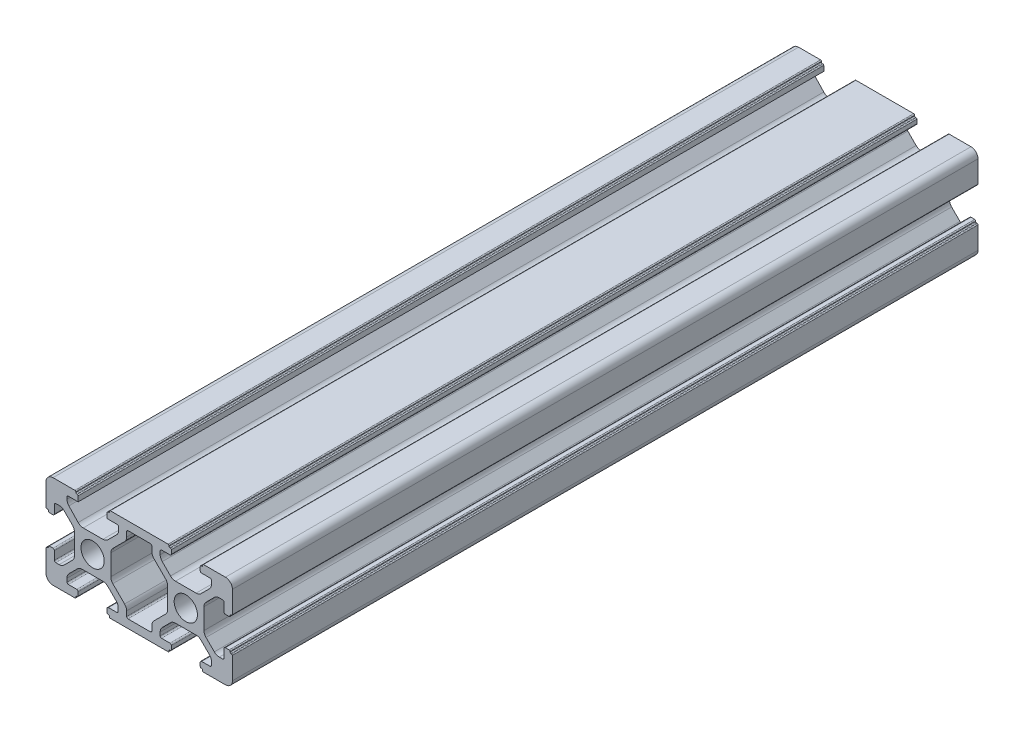
SolidWorks part; units mm, degrees
material "6063-T5"
ref_plane "Front Plane" through (0, 0, 0) normal (0, 0, 1) x (1, 0, 0)
ref_plane "Top Plane" through (0, 0, 0) normal (0, 1, 0) x (1, 0, 0)
ref_plane "Right Plane" through (0, 0, 0) normal (1, 0, 0) x (0, 0, -1)
sketch "Sketch1" plane through (0, 0, 0) normal (0, 0, 1) x (1, 0, 0)
  line L0 (1.5, 0) -> (6.2, 0)
  line L1 (40, 1.5) -> (40, 6.2)
  line L2 (38.5, 20) -> (33.8, 20)
  line L3 (0, 18.5) -> (0, 13.8)
  line L4 (17.6, 1.8) -> (22.4, 1.8)
  line L5 (32.218, 13.9) -> (27.782, 13.9)
  line L6 (26.1, 12.218) -> (26.1, 7.782)
  line L7 (17.6, 18.2) -> (22.4, 18.2)
  line L8 (12.218, 13.9) -> (7.9864, 13.9)
  line L9 (6.1, 12.218) -> (6.1, 7.782)
  line L10 (7.782, 6.1) -> (12.218, 6.1)
  line L11 (13.9, 7.782) -> (13.9, 12.218)
  line L12 (27.782, 6.1) -> (32.218, 6.1)
  line L13 (33.9, 7.782) -> (33.9, 12.218)
  line L14 (26.7213, 14.3393) -> (24.9393, 16.1213)
  line L15 (33.2787, 14.3393) -> (35.0607, 16.1213)
  line L16 (34.3393, 13.2787) -> (36.1213, 15.0607)
  line L17 (25.6607, 6.7213) -> (23.1393, 4.2)
  line L18 (15.2, 1.8) -> (13.4, 1.8)
  line L19 (26.7213, 5.6607) -> (24.9393, 3.8787)
  line L20 (24.8, 1.8) -> (26.6, 1.8)
  line L21 (15.3, 18.2) -> (13.1, 18.2)
  line L22 (13.2787, 14.3393) -> (15.1607, 16.2213)
  line L23 (14.3393, 13.2787) -> (16.8607, 15.8)
  line L24 (5.6607, 6.7213) -> (3.8787, 4.9393)
  line L25 (6.7213, 5.6607) -> (4.9393, 3.8787)
  line L26 (6.897, 14.3689) -> (4.9106, 16.4674)
  line L27 (5.6607, 13.2787) -> (3.8787, 15.0607)
  line L28 (14.3393, 6.7213) -> (16.8607, 4.2)
  line L29 (13.2787, 5.6607) -> (15.0607, 3.8787)
  line L30 (24.8, 18.2) -> (26.6, 18.2)
  line L31 (25.6607, 13.2787) -> (23.1393, 15.8)
  line L32 (34.3393, 6.7213) -> (36.1213, 4.9393)
  line L33 (33.2787, 5.6607) -> (35.0607, 3.8787)
  line L34 (1.8, 15.2) -> (1.8, 13.4)
  line L35 (24.5, 2.1) -> (24.5, 2.818)
  line L36 (4.5, 2.1) -> (4.5, 2.818)
  line L37 (2.818, 4.5) -> (2.1, 4.5)
  line L38 (4.5, 17.9) -> (4.5, 17.4986)
  line L39 (2.818, 15.5) -> (2.1, 15.5)
  line L40 (15.6, 17.9) -> (15.6, 17.282)
  line L41 (15.5, 2.818) -> (15.5, 2.1)
  line L42 (38.2, 15.2) -> (38.2, 13.4)
  line L43 (35.5, 2.818) -> (35.5, 2.1)
  line L44 (37.182, 4.5) -> (37.9, 4.5)
  line L45 (35.5, 17.182) -> (35.5, 17.9)
  line L46 (37.182, 15.5) -> (37.9, 15.5)
  line L47 (17.3, 2.1) -> (17.3, 3.1393)
  line L48 (22.7, 2.1) -> (22.7, 3.1393)
  line L49 (17.3, 17.9) -> (17.3, 16.8607)
  line L50 (22.7, 17.9) -> (22.7, 16.8607)
  line L51 (24.5, 17.9) -> (24.5, 17.182)
  line L52 (6.9, 19.3) -> (6.9, 18.2)
  line L53 (13.1, 19.3) -> (13.1, 18.2)
  line L54 (6.9, 1.5) -> (6.9, 0.7)
  line L55 (13.1, 1.5) -> (13.1, 0.7)
  line L56 (13.8, 0) -> (26.2, 0)
  line L57 (6.6, 1.8) -> (4.8, 1.8)
  line L58 (6.9, 18.2) -> (4.8, 18.2)
  line L59 (6.2, 20) -> (1.5, 20)
  line L60 (39.3, 6.9) -> (38.5, 6.9)
  line L61 (39.3, 13.1) -> (38.5, 13.1)
  line L62 (1.5, 13.1) -> (0.7, 13.1)
  line L63 (1.5, 6.9) -> (0.7, 6.9)
  line L64 (0, 6.2) -> (0, 1.5)
  line L65 (1.8, 6.6) -> (1.8, 4.8)
  line L66 (38.2, 6.6) -> (38.2, 4.8)
  line L67 (40, 13.8) -> (40, 18.5)
  line L68 (33.1, 19.3) -> (33.1, 18.5)
  line L69 (26.9, 19.3) -> (26.9, 18.5)
  line L70 (26.9, 1.5) -> (26.9, 0.7)
  line L71 (33.1, 1.5) -> (33.1, 0.7)
  line L72 (33.8, 0) -> (38.5, 0)
  line L73 (33.4, 1.8) -> (35.2, 1.8)
  line L74 (26.2, 20) -> (13.8, 20)
  line L75 (33.4, 18.2) -> (35.2, 18.2)
  line L76 (6.7, 0.5) -> (6.6, 0.5)
  line L77 (6.4, 0.3) -> (6.4, 0.2)
  line L78 (13.3, 0.5) -> (13.4, 0.5)
  line L79 (13.6, 0.3) -> (13.6, 0.2)
  line L80 (26.7, 0.5) -> (26.6, 0.5)
  line L81 (26.4, 0.3) -> (26.4, 0.2)
  line L82 (33.3, 0.5) -> (33.4, 0.5)
  line L83 (33.6, 0.3) -> (33.6, 0.2)
  line L85 (6.4, 19.8) -> (6.4, 19.7)
  line L86 (6.6, 19.5) -> (6.7, 19.5)
  line L87 (13.6, 19.8) -> (13.6, 19.7)
  line L88 (13.4, 19.5) -> (13.3, 19.5)
  line L89 (26.4, 19.8) -> (26.4, 19.7)
  line L90 (26.6, 19.5) -> (26.7, 19.5)
  line L91 (33.6, 19.8) -> (33.6, 19.7)
  line L92 (33.4, 19.5) -> (33.3, 19.5)
  line L93 (0.5, 13.3) -> (0.5, 13.4)
  line L94 (0.3, 13.6) -> (0.2, 13.6)
  line L95 (0.5, 6.7) -> (0.5, 6.6)
  line L96 (0.3, 6.4) -> (0.2, 6.4)
  line L97 (39.5, 13.3) -> (39.5, 13.4)
  line L98 (39.7, 13.6) -> (39.8, 13.6)
  line L99 (39.5, 6.7) -> (39.5, 6.6)
  line L100 (39.7, 6.4) -> (39.8, 6.4)
  circle A0 centre (10, 10) radius 2.5
  circle A1 centre (30, 10) radius 2.5
  arc A2 (38.5, 0) -> (40, 1.5) centre (38.5, 1.5) ccw
  arc A3 (40, 18.5) -> (38.5, 20) centre (38.5, 18.5) ccw
  arc A4 (1.5, 0) -> (0, 1.5) centre (1.5, 1.5) cw
  arc A5 (1.5, 20) -> (0, 18.5) centre (1.5, 18.5) ccw
  arc A6 (26.7213, 5.6607) -> (27.782, 6.1) centre (27.782, 4.6) cw
  arc A7 (32.218, 6.1) -> (33.2787, 5.6607) centre (32.218, 4.6) cw
  arc A8 (33.9, 7.782) -> (34.3393, 6.7213) centre (35.4, 7.782) ccw
  arc A9 (33.2787, 14.3393) -> (32.218, 13.9) centre (32.218, 15.4) cw
  arc A10 (14.3393, 6.7213) -> (13.9, 7.782) centre (15.4, 7.782) cw
  arc A11 (14.3393, 13.2787) -> (13.9, 12.218) centre (15.4, 12.218) ccw
  arc A12 (25.6607, 6.7213) -> (26.1, 7.782) centre (24.6, 7.782) ccw
  arc A13 (26.1, 12.218) -> (25.6607, 13.2787) centre (24.6, 12.218) ccw
  arc A14 (27.782, 13.9) -> (26.7213, 14.3393) centre (27.782, 15.4) cw
  arc A15 (5.6607, 13.2787) -> (6.1, 12.218) centre (4.6, 12.218) cw
  arc A16 (5.6607, 6.7213) -> (6.1, 7.782) centre (4.6, 7.782) ccw
  arc A17 (13.2787, 5.6607) -> (12.218, 6.1) centre (12.218, 4.6) ccw
  arc A18 (6.7213, 5.6607) -> (7.782, 6.1) centre (7.782, 4.6) cw
  arc A19 (13.2787, 14.3393) -> (12.218, 13.9) centre (12.218, 15.4) cw
  arc A20 (6.897, 14.3689) -> (7.9864, 13.9) centre (7.9864, 15.4) ccw
  arc A21 (36.1213, 4.9393) -> (37.182, 4.5) centre (37.182, 6) ccw
  arc A22 (36.1213, 15.0607) -> (37.182, 15.5) centre (37.182, 14) cw
  arc A23 (35.0607, 16.1213) -> (35.5, 17.182) centre (34, 17.182) ccw
  arc A24 (24.5, 17.182) -> (24.9393, 16.1213) centre (26, 17.182) ccw
  arc A25 (22.7, 16.8607) -> (23.1393, 15.8) centre (24.2, 16.8607) ccw
  arc A26 (17.3, 16.8607) -> (16.8607, 15.8) centre (15.8, 16.8607) cw
  arc A27 (4.9106, 16.4674) -> (4.5, 17.4986) centre (6, 17.4986) cw
  arc A28 (15.6, 17.282) -> (15.1607, 16.2213) centre (14.1, 17.282) cw
  arc A29 (3.8787, 15.0607) -> (2.818, 15.5) centre (2.818, 14) ccw
  arc A30 (3.8787, 4.9393) -> (2.818, 4.5) centre (2.818, 6) cw
  arc A31 (4.9393, 3.8787) -> (4.5, 2.818) centre (6, 2.818) ccw
  arc A32 (35.0607, 3.8787) -> (35.5, 2.818) centre (34, 2.818) cw
  arc A33 (24.9393, 3.8787) -> (24.5, 2.818) centre (26, 2.818) ccw
  arc A34 (22.7, 3.1393) -> (23.1393, 4.2) centre (24.2, 3.1393) cw
  arc A35 (17.3, 3.1393) -> (16.8607, 4.2) centre (15.8, 3.1393) ccw
  arc A36 (15.5, 2.818) -> (15.0607, 3.8787) centre (14, 2.818) ccw
  arc A37 (1.8, 6.6) -> (1.5, 6.9) centre (1.5, 6.6) ccw
  arc A38 (1.8, 13.4) -> (1.5, 13.1) centre (1.5, 13.4) cw
  arc A39 (17.6, 18.2) -> (17.3, 17.9) centre (17.6, 17.9) ccw
  arc A40 (22.4, 1.8) -> (22.7, 2.1) centre (22.4, 2.1) ccw
  arc A41 (17.6, 1.8) -> (17.3, 2.1) centre (17.6, 2.1) cw
  arc A42 (15.2, 1.8) -> (15.5, 2.1) centre (15.2, 2.1) ccw
  arc A43 (6.6, 1.8) -> (6.9, 1.5) centre (6.6, 1.5) cw
  arc A44 (13.4, 1.8) -> (13.1, 1.5) centre (13.4, 1.5) ccw
  arc A45 (24.8, 1.8) -> (24.5, 2.1) centre (24.8, 2.1) cw
  arc A46 (35.2, 1.8) -> (35.5, 2.1) centre (35.2, 2.1) ccw
  arc A47 (26.6, 1.8) -> (26.9, 1.5) centre (26.6, 1.5) cw
  arc A48 (33.4, 1.8) -> (33.1, 1.5) centre (33.4, 1.5) ccw
  arc A49 (26.9, 18.5) -> (26.6, 18.2) centre (26.6, 18.5) cw
  arc A50 (33.1, 18.5) -> (33.4, 18.2) centre (33.4, 18.5) ccw
  arc A51 (37.9, 4.5) -> (38.2, 4.8) centre (37.9, 4.8) ccw
  arc A52 (38.5, 13.1) -> (38.2, 13.4) centre (38.5, 13.4) cw
  arc A53 (38.5, 6.9) -> (38.2, 6.6) centre (38.5, 6.6) ccw
  arc A54 (38.2, 15.2) -> (37.9, 15.5) centre (37.9, 15.2) ccw
  arc A55 (35.2, 18.2) -> (35.5, 17.9) centre (35.2, 17.9) cw
  arc A56 (24.8, 18.2) -> (24.5, 17.9) centre (24.8, 17.9) ccw
  arc A57 (22.4, 18.2) -> (22.7, 17.9) centre (22.4, 17.9) cw
  arc A58 (15.3, 18.2) -> (15.6, 17.9) centre (15.3, 17.9) cw
  arc A59 (4.5, 17.9) -> (4.8, 18.2) centre (4.8, 17.9) cw
  arc A60 (1.8, 15.2) -> (2.1, 15.5) centre (2.1, 15.2) cw
  arc A61 (1.8, 4.8) -> (2.1, 4.5) centre (2.1, 4.8) ccw
  arc A62 (4.5, 2.1) -> (4.8, 1.8) centre (4.8, 2.1) ccw
  arc A63 (34.3393, 13.2787) -> (33.9, 12.218) centre (35.4, 12.218) ccw
  arc A64 (6.4, 0.2) -> (6.2, 0) centre (6.2, 0.2) cw
  arc A65 (6.6, 0.5) -> (6.4, 0.3) centre (6.6, 0.3) ccw
  arc A66 (6.7, 0.5) -> (6.9, 0.7) centre (6.7, 0.7) ccw
  arc A67 (13.6, 0.2) -> (13.8, 0) centre (13.8, 0.2) ccw
  arc A68 (13.4, 0.5) -> (13.6, 0.3) centre (13.4, 0.3) cw
  arc A69 (13.3, 0.5) -> (13.1, 0.7) centre (13.3, 0.7) cw
  arc A70 (26.4, 0.2) -> (26.2, 0) centre (26.2, 0.2) cw
  arc A71 (26.6, 0.5) -> (26.4, 0.3) centre (26.6, 0.3) ccw
  arc A72 (26.7, 0.5) -> (26.9, 0.7) centre (26.7, 0.7) ccw
  arc A73 (33.6, 0.2) -> (33.8, 0) centre (33.8, 0.2) ccw
  arc A74 (33.4, 0.5) -> (33.6, 0.3) centre (33.4, 0.3) cw
  arc A75 (33.3, 0.5) -> (33.1, 0.7) centre (33.3, 0.7) cw
  arc A76 (39.8, 6.4) -> (40, 6.2) centre (39.8, 6.2) cw
  arc A77 (39.5, 6.6) -> (39.7, 6.4) centre (39.7, 6.6) ccw
  arc A78 (39.5, 6.7) -> (39.3, 6.9) centre (39.3, 6.7) ccw
  arc A79 (39.5, 13.3) -> (39.3, 13.1) centre (39.3, 13.3) cw
  arc A80 (39.5, 13.4) -> (39.7, 13.6) centre (39.7, 13.4) cw
  arc A81 (39.8, 13.6) -> (40, 13.8) centre (39.8, 13.8) ccw
  arc A82 (33.3, 19.5) -> (33.1, 19.3) centre (33.3, 19.3) ccw
  arc A83 (33.6, 19.7) -> (33.4, 19.5) centre (33.4, 19.7) cw
  arc A84 (33.6, 19.8) -> (33.8, 20) centre (33.8, 19.8) cw
  arc A85 (26.7, 19.5) -> (26.9, 19.3) centre (26.7, 19.3) cw
  arc A86 (26.4, 19.7) -> (26.6, 19.5) centre (26.6, 19.7) ccw
  arc A87 (26.4, 19.8) -> (26.2, 20) centre (26.2, 19.8) ccw
  arc A88 (0.2, 6.4) -> (0, 6.2) centre (0.2, 6.2) ccw
  arc A89 (0.5, 6.6) -> (0.3, 6.4) centre (0.3, 6.6) cw
  arc A90 (0.5, 6.7) -> (0.7, 6.9) centre (0.7, 6.7) cw
  arc A91 (13.3, 19.5) -> (13.1, 19.3) centre (13.3, 19.3) ccw
  arc A92 (13.6, 19.7) -> (13.4, 19.5) centre (13.4, 19.7) cw
  arc A93 (13.6, 19.8) -> (13.8, 20) centre (13.8, 19.8) cw
  arc A94 (6.2, 20) -> (6.4, 19.8) centre (6.2, 19.8) cw
  arc A95 (6.7, 19.5) -> (6.9, 19.3) centre (6.7, 19.3) cw
  arc A96 (6.4, 19.7) -> (6.6, 19.5) centre (6.6, 19.7) ccw
  arc A97 (0.5, 13.3) -> (0.7, 13.1) centre (0.7, 13.3) ccw
  arc A98 (0.2, 13.6) -> (0, 13.8) centre (0.2, 13.8) cw
  arc A99 (0.5, 13.4) -> (0.3, 13.6) centre (0.3, 13.4) ccw
  point P87 (0, 0)
  point P178 (1.8, 6.9)
  point P181 (1.8, 13.1)
  point P186 (22.7, 1.8)
  point P193 (6.9, 1.8)
  point P204 (33.1, 1.8)
  point P209 (33.1, 18.2)
  point P216 (38.2, 6.9)
  point P243 (6.9, 0.5)
  point P248 (13.6, 0.5)
  point P257 (26.9, 0.5)
extrude "Boss-Extrude2" add sketch "Sketch1" along normal blind 160 contours A57 L7 A39 L49 A26 L23 A11 L11 A10 L28 A35 L47 A41 L4 A40 L48 A34 L17 A12 L6 A13 L31 A25 L50 | A0 | A1 | L59 A5 L3 A98 L94 A99 L93 A97 L62 A38 L34 A60 L39 A29 L27 A15 L9 A16 L24 A30 L37 A61 L65 A37 L63 A90 L95 A89 L96 A88 L64 A4 L0 A64 L77 A65 L76 A66 L54 A43 L57 A62 L36 A31 L25 A18 L10 A17 L29 A36 L41 A42 L18 A44 L55 A69 L78 A68 L79 A67 L56 A70 L81 A71 L80 A72 L70 A47 L20 A45 L35 A33 L19 A6 L12 A7 L33 A32 L43 A46 L73 A48 L71 A75 L82 A74 L83 A73 L72 A2 L1 A76 L100 A77 L99 A78 L60 A53 L66 A51 L44 A21 L32 A8 L13 A63 L16 A22 L46 A54 L42 A52 L61 A79 L97 A80 L98 A81 L67 A3 L2 A84 L91 A83 L92 A82 L68 A50 L75 A55 L45 A23 L15 A9 L5 A14 L14 A24 L51 A56 L30 A49 L69 A85 L90 A86 L89 A87 L74 A93 L87 A92 L88 A91 L53 L21 A58 L40 A28 L22 A19 L8 A20 L26 A27 L38 A59 L58 L52 A95 L86 A96 L85 A94
